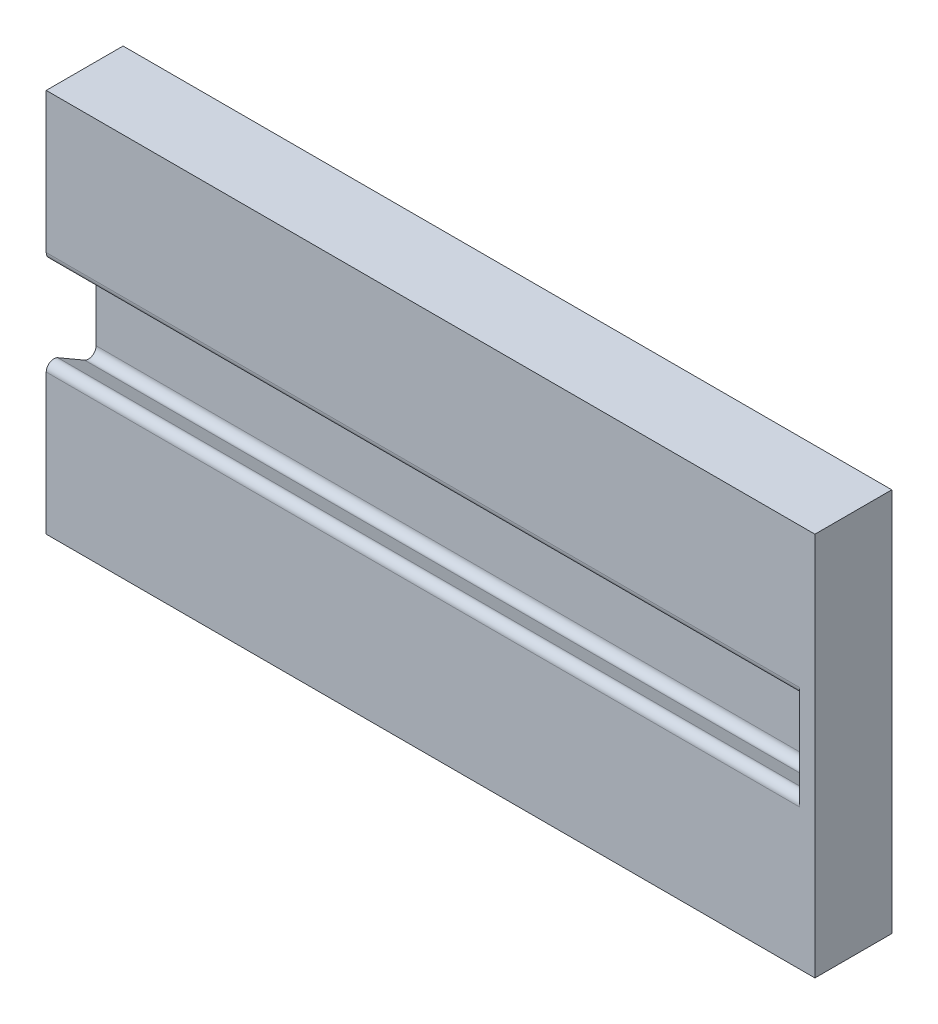
SolidWorks part; units mm, degrees
ref_plane "Ön Düzlem" through (0, 0, 0) normal (0, 0, 1) x (1, 0, 0)
ref_plane "Üst Düzlem" through (0, 0, 0) normal (0, 1, 0) x (1, 0, 0)
ref_plane "Sağ Düzlem" through (0, 0, 0) normal (1, 0, 0) x (0, 0, -1)
sketch "Çizim1" plane through (0, 0, 0) normal (0, 0, 1) x (1, 0, 0)
  line L1 (-50, 25) -> (50, 25)
  line L2 (-50, 25) -> (-50, -25)
  line L3 (-50, -25) -> (50, -25)
  line L4 (50, 25) -> (50, -25)
  line L5 (-50, 25) -> (50, -25) construction
  line L6 (-50, -25) -> (50, 25) construction
  point P0 (0, 0)
  dimension "D1" = 100
  dimension "D2" = 50
extrude "Yükseklik-Ekstrüzyon1" add sketch "Çizim1" along normal blind 10
sketch "Çizim2" plane through (-50, 0, 0) normal (-1, 0, 0) x (0, 0, 1)
  line L0 (10, 5) -> (3.5048, 8.75)
  line L1 (10, 25) -> (10, -25) construction
  line L2 (3.5048, 8.75) -> (3.5048, -8.75)
  line L3 (5.5, 0) -> (-5.5, 0) construction
  line L4 (10, -5) -> (3.5048, -8.75)
  line L5 (10, -5) -> (10, 5)
  point P4 (3.5048, 0)
  dimension "D1" = 60
  dimension "D2" = 7.5
  dimension "D3" = 5
extrude "Kes-Ekstrüzyon1" cut sketch "Çizim2" against normal offset from surface (98 mm away) 2 up to face at (50, 0, 5)
fillet "Radyus1" radius 1 4 edges at (-1, -8.75, 3.5048) (-1, 8.75, 3.5048) (-1, -5, 10) (-1, 5, 10)
